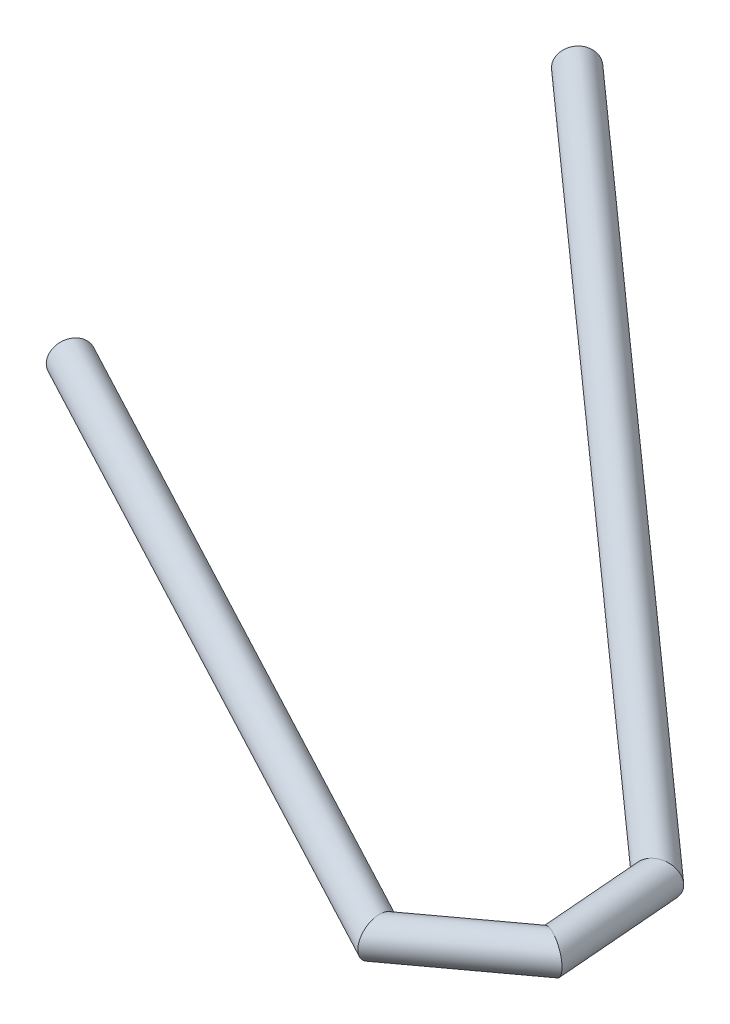
SolidWorks part; units mm, degrees
material "Plain Carbon Steel"
ref_plane "Front Plane" through (0, 0, 0) normal (0, 0, 1) x (1, 0, 0)
ref_plane "Top Plane" through (0, 0, 0) normal (0, 1, 0) x (1, 0, 0)
ref_plane "Right Plane" through (0, 0, 0) normal (1, 0, 0) x (0, 0, -1)
ref_plane "Plane1" through (0, 39.1414, 0) normal (0, 1, 0) x (-1, 0, 0)
sketch "Sketch1" plane through (0, 39.1414, 0) normal (0, 1, 0) x (-1, 0, 0)
  line L0 (141.9597, 22.7043) -> (-86.0208, 143.5748)
  line L1 (-86.0208, 143.5748) -> (-120.9994, 117.8276)
  line L2 (-120.9994, 117.8276) -> (-117.755, 77.6576)
  line L3 (-117.755, 77.6576) -> (141.9597, -154.0146)
ref_plane "Plane2" through (-141.9597, 39.1414, -154.0146) normal (-0.7462, 0, -0.6657) x (-0.6657, 0, 0.7462)
sketch "Sketch3" plane through (-141.9597, 39.1414, -154.0146) normal (-0.7462, 0, -0.6657) x (-0.6657, 0, 0.7462)
  line L0 (27.817, 0) -> (0, 0) construction
  circle A0 centre (0, 0) radius 6.352
sweep "Sweep1" add profiles "Sketch3" path "Sketch1"
